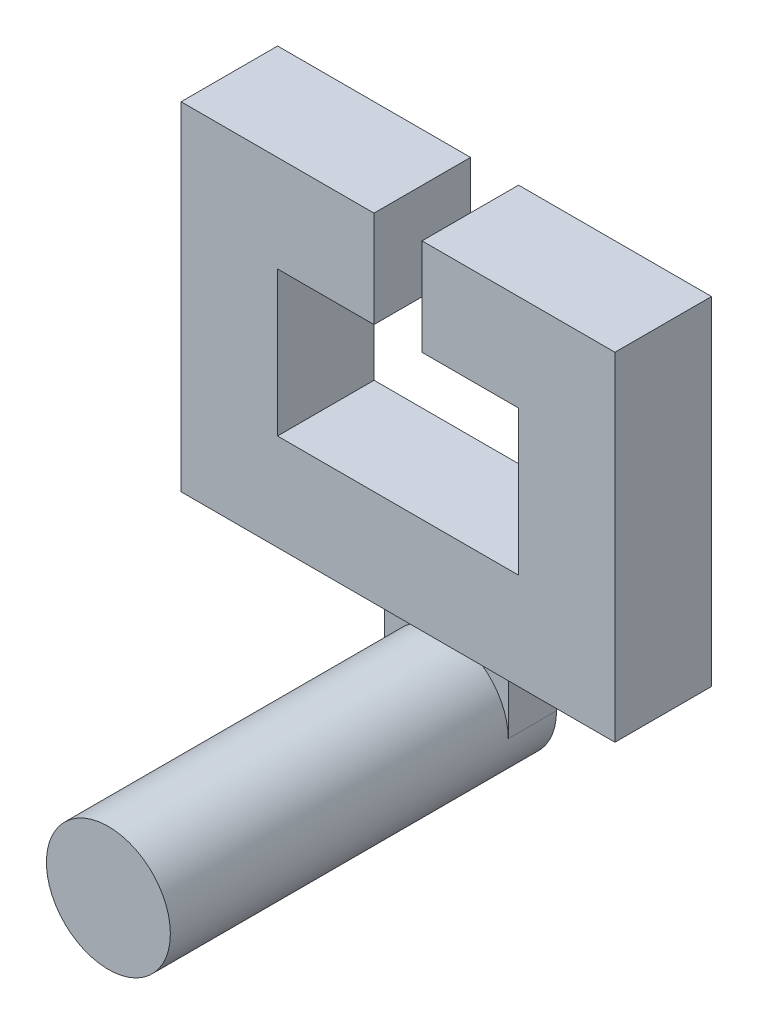
SolidWorks part; units mm, degrees
ref_plane "Front Plane" through (0, 0, 0) normal (0, 0, 1) x (1, 0, 0)
ref_plane "Top Plane" through (0, 0, 0) normal (0, 1, 0) x (1, 0, 0)
ref_plane "Right Plane" through (0, 0, 0) normal (1, 0, 0) x (0, 0, -1)
sketch "Sketch1" plane through (0, 0, 0) normal (0, 0, 1) x (1, 0, 0)
  circle A0 centre (0, 0) radius 16.3068
  dimension "D1" = 32.6136
extrude "Feature A" add sketch "Sketch1" along normal blind 101.6
sketch "Sketch2" plane through (0, 0, 0) normal (0, 1, 0) x (1, 0, 0)
  line L0 (16.3068, -101.6) -> (16.3068, 0) construction
  line L1 (-16.3068, 0) -> (16.3068, 0)
  line L2 (-16.3068, 0) -> (-16.3068, -12.7)
  line L3 (-16.3068, -12.7) -> (16.3068, -12.7)
  line L4 (16.3068, 0) -> (16.3068, -12.7)
  dimension "D1" = 12.7
extrude "Feature B" add sketch "Sketch2" along normal blind 25.908
sketch "Sketch3" plane through (0, 25.908, 0) normal (0, 1, 0) x (1, 0, 0)
  line L1 (-31.6992, 0) -> (31.6992, 0)
  line L2 (-31.6992, 0) -> (-31.6992, -25.4)
  line L3 (-31.6992, -25.4) -> (31.6992, -25.4)
  line L4 (31.6992, 0) -> (31.6992, -25.4)
  line L5 (16.3068, 0) -> (-16.3068, 0) construction
  point P4 (0, 0)
  dimension "D1" = 63.3984
  dimension "D2" = 25.4
extrude "Feature C" add sketch "Sketch3" along normal blind 25.4
sketch "Sketch4" plane through (31.6992, 0, 0) normal (1, 0, 0) x (0, 0, -1)
  line L1 (-25.4, 25.908) -> (0, 25.908)
  line L2 (-25.4, 25.908) -> (-25.4, 89.3826)
  line L3 (-25.4, 89.3826) -> (0, 89.3826)
  line L4 (0, 25.908) -> (0, 89.3826)
  dimension "D2" = 25.4
  dimension "D1" = 63.4746
extrude "Feature D" add sketch "Sketch4" along normal blind 25.3746
sketch "Sketch5" plane through (0, 89.3826, 0) normal (0, 1, 0) x (1, 0, 0)
  line L0 (-31.6992, -25.4) -> (31.6992, -25.4) construction
  line L1 (57.0738, 0) -> (6.3195, 0)
  line L2 (57.0738, 0) -> (57.0738, -25.4)
  line L3 (57.0738, -25.4) -> (6.3195, -25.4)
  line L4 (6.3195, 0) -> (6.3195, -25.4)
  dimension "D1" = 50.7543
extrude "Feature E" add sketch "Sketch5" along normal blind 25.4
ref_point "Point4"
ref_plane "Plane3" through (0, 0, 0) normal (-1, 0, 0) x (0, 0, 1)
mirror "Mirror6" about plane through (0, 0, 0) normal (-1, 0, 0) of "Feature C", "Feature D", "Feature E"
equation "\"La\" = 4'Length of Feature a [in]"
equation "\"Ra\"= .6420'Radius of Feature a [in]"
equation "\"Lb\"= 1.02'Length of B [in]"
equation "\"Wb\"= \"Dr\"'Width of B [in]"
equation "\"Tb\" = .5'Thickness of feature B [in]"
equation "\"Tcde\"= 1'Thickness of features C,D, E [in]"
equation "\"Ld\" = 1.499 + \"Lc\"'Length of feature D [in]"
equation "\"Wd\"= .999'Width of feature D [in]"
equation "\"Wc\" = 2.496'Width of feature C [in]"
equation "\"Lc\"= 1'Length of feature C [in]"
equation "\"We\"= .9992'width of feature E [in]"
equation "\"Le\"= 1'Length of Feature E [In]"
equation "\"Dr\"= \"Ra\" * 2'Diameter of feature A [ in]"
equation "\"D1@Sketch1\"= \"Dr\""
equation "\"D1@Feature A\" = \"La\""
equation "\"D1@Sketch2\"=\"Tb\""
equation "\"D1@Feature B\" = \"Lb\""
equation "\"D1@Sketch3\"=\"Wc\""
equation "\"D2@Sketch3\"= \"Tcde\""
equation "\"D1@Feature C\" = \"Lc\""
equation "\"D1@Sketch4\"=\"Ld\""
equation "\"D2@Sketch4\"= \"Tcde\""
equation "\"D1@Feature D\" = \"Wd\""
equation "\"D1@Sketch5\"=\"We\"+\"Wd\""
equation "\"D1@Feature E\" = \"Le\""
